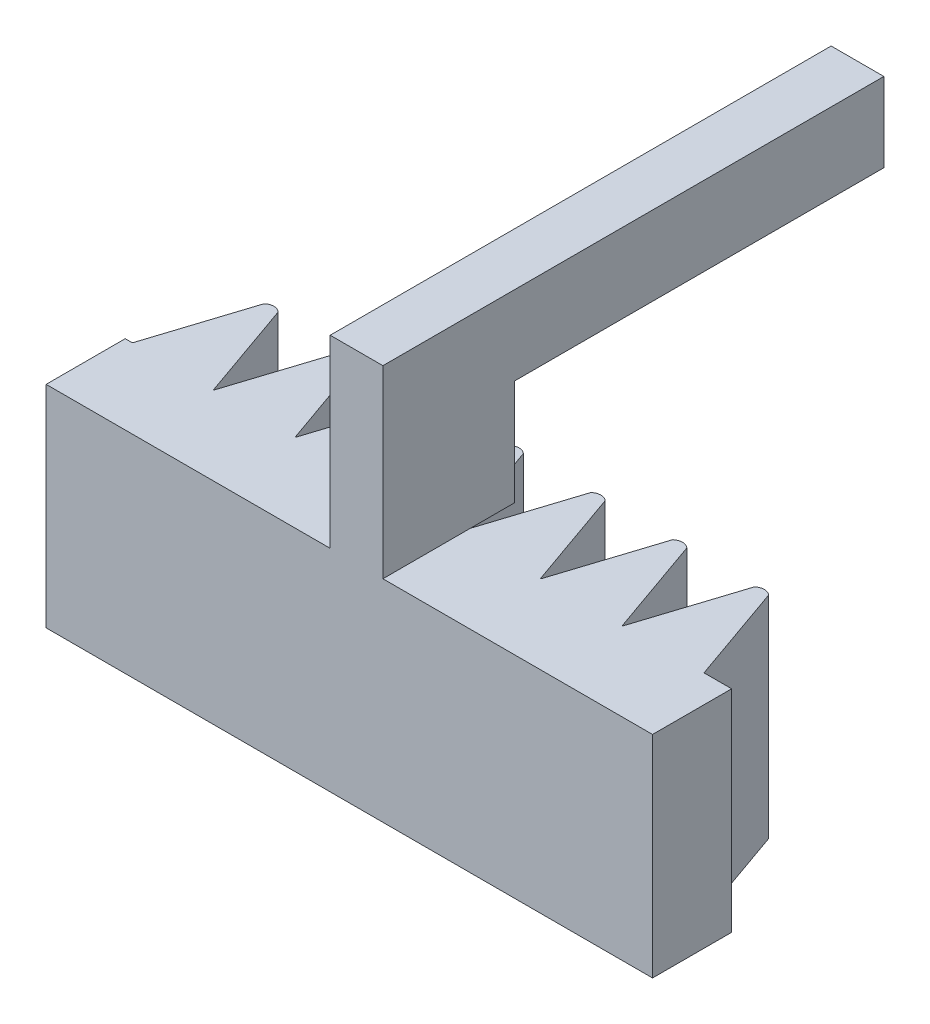
SolidWorks part; units mm, degrees
ref_plane "Front Plane" through (0, 0, 0) normal (0, 0, 1) x (1, 0, 0)
ref_plane "Top Plane" through (0, 0, 0) normal (0, 1, 0) x (1, 0, 0)
ref_plane "Right Plane" through (0, 0, 0) normal (1, 0, 0) x (0, 0, -1)
sketch "Base" plane through (0, 0, 0) normal (0, 1, 0) x (1, 0, 0)
  line L1 (-0.7735, 0) -> (22.2265, 0)
  line L2 (-0.7735, 0) -> (-0.7735, -3)
  line L3 (-0.7735, -3) -> (22.2265, -3)
  line L4 (22.2265, 0) -> (22.2265, -3)
  dimension "D1" = 23
  dimension "D2" = 3
sketch "Gears-1" plane through (0, 0, 0) normal (0, 1, 0) x (1, 0, 0)
  line L0 (-0.5006, 0) -> (0.7096, 3.7758)
  line L1 (-0.7735, 0) -> (22.2265, 0) construction
  line L2 (0.9805, 3.883) -> (0.9805, 2.653) construction
  line L3 (2.579, 0) -> (1.2514, 3.7758)
  line L4 (-0.5006, 0) -> (2.579, 0)
  line L5 (2.5994, 0) -> (5.679, 0)
  line L6 (5.679, 0) -> (4.3514, 3.7758)
  line L7 (2.5994, 0) -> (3.8096, 3.7758)
  line L8 (5.6994, 0) -> (8.779, 0)
  line L9 (8.779, 0) -> (7.4514, 3.7758)
  line L10 (5.6994, 0) -> (6.9096, 3.7758)
  line L11 (8.7994, 0) -> (11.879, 0)
  line L12 (11.879, 0) -> (10.5514, 3.7758)
  line L13 (8.7994, 0) -> (10.0096, 3.7758)
  line L14 (11.8994, 0) -> (14.979, 0)
  line L15 (14.979, 0) -> (13.6514, 3.7758)
  line L16 (11.8994, 0) -> (13.1096, 3.7758)
  line L17 (14.9994, 0) -> (18.079, 0)
  line L18 (18.079, 0) -> (16.7514, 3.7758)
  line L19 (14.9994, 0) -> (16.2096, 3.7758)
  line L20 (18.0994, 0) -> (21.179, 0)
  line L21 (21.179, 0) -> (19.8514, 3.7758)
  line L22 (18.0994, 0) -> (19.3096, 3.7758)
  arc A0 (0.7096, 3.7758) -> (1.2514, 3.7758) centre (0.9805, 3.4871) cw
  arc A1 (3.8096, 3.7758) -> (4.3514, 3.7758) centre (4.0805, 3.4871) cw
  arc A2 (6.9096, 3.7758) -> (7.4514, 3.7758) centre (7.1805, 3.4871) cw
  arc A3 (10.0096, 3.7758) -> (10.5514, 3.7758) centre (10.2805, 3.4871) cw
  arc A4 (13.1096, 3.7758) -> (13.6514, 3.7758) centre (13.3805, 3.4871) cw
  arc A5 (16.2096, 3.7758) -> (16.7514, 3.7758) centre (16.4805, 3.4871) cw
  arc A6 (19.3096, 3.7758) -> (19.8514, 3.7758) centre (19.5805, 3.4871) cw
  dimension "D1" = 7
extrude "Boss-Extrude1" add sketch "Gears-1" along normal blind 8
extrude "Boss-Extrude2" add sketch "Base" along normal blind 8
ref_plane "Plane1" through (10, 0, 0) normal (1, 0, 0) x (0, 0, -1)
sketch "Sketch1" plane through (10, 0, 0) normal (1, 0, 0) x (0, 0, -1)
  line L1 (-3, 8) -> (2, 8)
  line L2 (-3, 8) -> (-3, 15)
  line L3 (-3, 15) -> (2, 15)
  line L4 (2, 8) -> (2, 15)
  point P4 (3.8672, 6)
  point P5 (0, 0)
  dimension "D1" = 7
  dimension "D2" = 5
extrude "Boss-Extrude3" add sketch "Sketch1" along normal blind 2
sketch "Sketch2" plane through (0, 0, -2) normal (0, 0, -1) x (-1, 0, 0)
  line L0 (-10, 8) -> (-10, 15) construction
  line L1 (-12, 15) -> (-10, 15)
  line L2 (-12, 15) -> (-12, 12)
  line L3 (-12, 12) -> (-10, 12)
  line L4 (-10, 15) -> (-10, 12)
  dimension "D1" = 3
extrude "Boss-Extrude4" add sketch "Sketch2" along normal blind 14
